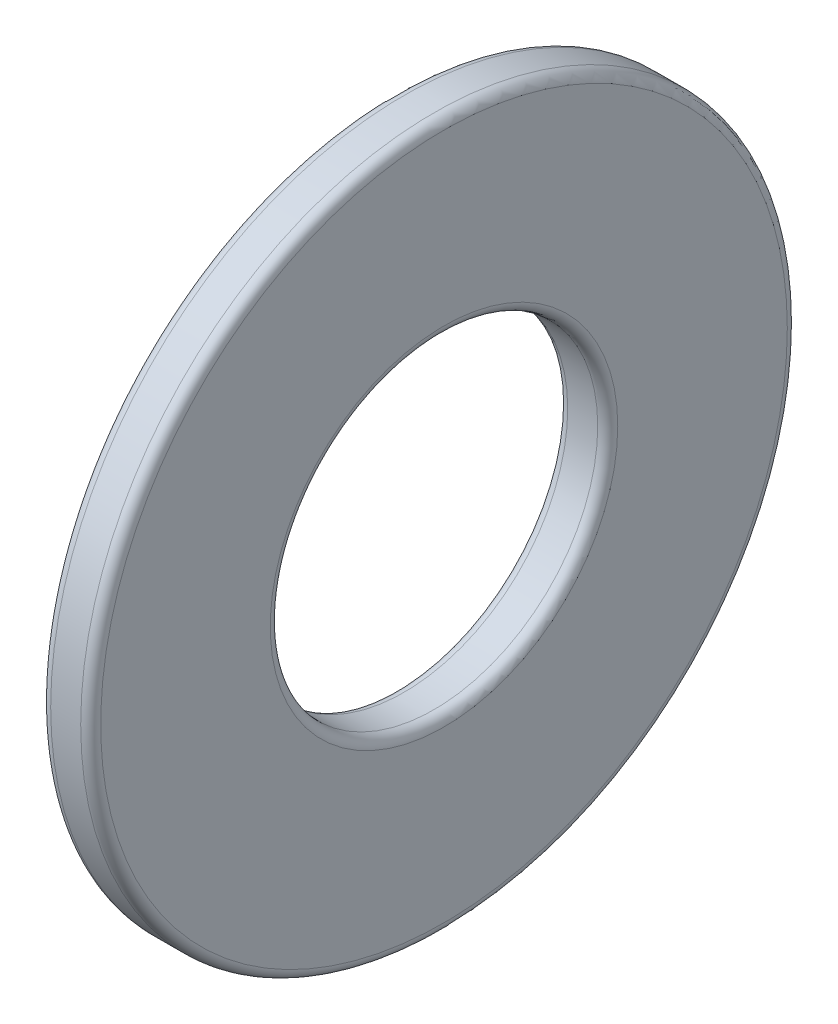
SolidWorks part; units mm, degrees
ref_plane "Front Plane" through (0, 0, 0) normal (0, 0, 1) x (1, 0, 0)
ref_plane "Top Plane" through (0, 0, 0) normal (0, 1, 0) x (1, 0, 0)
ref_plane "Right Plane" through (0, 0, 0) normal (1, 0, 0) x (0, 0, -1)
sketch "Sketch3" plane through (0, 0, 0) normal (0, 0, 1) x (1, 0, 0)
  line L0 (-0.3937, 0) -> (0.3937, 0) construction
  line L1 (0, -5.5626) -> (0, 5.5626) construction
  line L2 (0, -2.5781) -> (0, 2.5781) construction
  line L4 (0.3937, -5.5626) -> (-0.3937, -5.5626)
  line L5 (0.3937, -5.5626) -> (0.3937, 5.5626)
  line L6 (0.3937, 5.5626) -> (-0.3937, 5.5626)
  line L7 (-0.3937, -5.5626) -> (-0.3937, 5.5626)
  line L8 (0, 5.5626) -> (0, -5.5626) construction
  line L9 (0.3937, 0) -> (-0.3937, 0) construction
  point P0 (0, 0)
  point P4 (0, 0)
  point P8 (0, 0)
  point P11 (0, 0)
  dimension "ID" = 5.1562
  dimension "OD" = 11.1252
  dimension "Thickness" = 0.7874
sketch "Sketch1" plane through (0, 0, 0) normal (1, 0, 0) x (0, 0, -1)
  circle A0 centre (0, 0) radius 5.5626
  circle A1 centre (0, 0) radius 2.5781
extrude "Boss-Extrude1" add sketch "Sketch1" along normal mid plane 0.7874
fillet "Fillet1" radius 0.1575 4 edges at (0.3937, 0, -5.5626) (-0.3937, 0, -5.5626) (0.3937, 0, -2.5781) (-0.3937, 0, -2.5781)
sketch "Sketch4" plane through (-0.3937, 0, 0) normal (-1, 0, 0) x (0, 0, 1)
  line L0 (0, -5.5626) -> (0, 5.5626) construction
  line L1 (0, -5.5626) -> (0, 5.5626) construction
  circle A0 centre (0, 0) radius 2.5781 construction
  circle A1 centre (0, 0) radius 5.5626 construction
  circle A2 centre (0, 0) radius 2.5781 construction
  circle A3 centre (0, 0) radius 5.5626 construction
  point P0 (0, -2.5781)
  point P1 (0, 2.5781)
  point P5 (-5.5626, 0)
  point P9 (-2.5781, 0)
  point P10 (2.5781, 0)
  point P11 (5.5626, 0)
equation "\"D1@Boss-Extrude1\" = \"Thickness@Sketch3\""
equation "\"D1@Fillet1\"=\"Thickness@Sketch3\"*.2"
